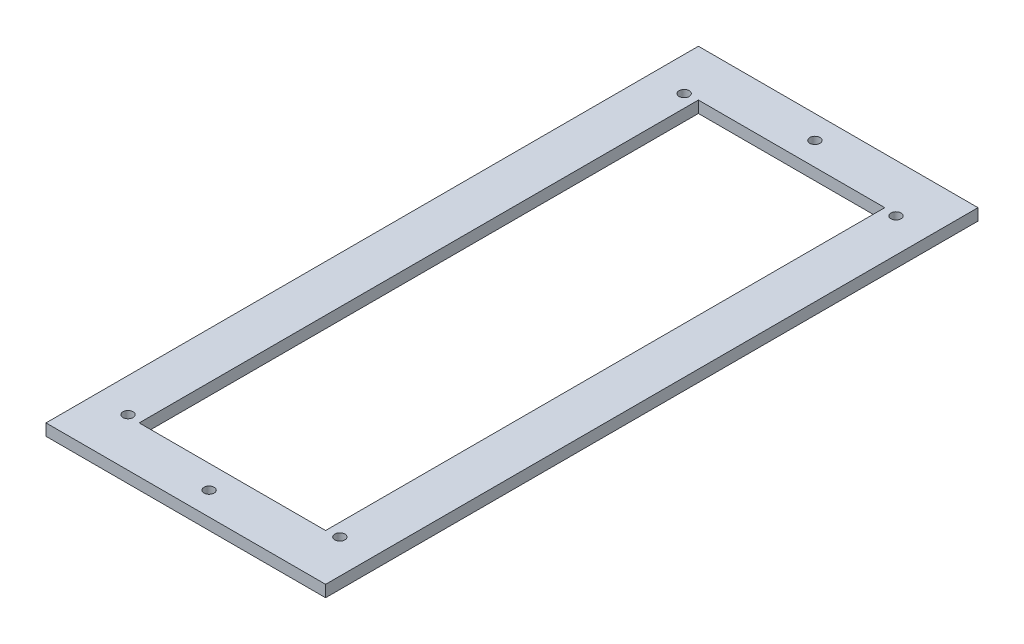
SolidWorks part; units mm, degrees
material "Birch Ply"
ref_plane "Front Plane" through (0, 0, 0) normal (0, 0, 1) x (1, 0, 0)
ref_plane "Top Plane" through (0, 0, 0) normal (0, 1, 0) x (1, 0, 0)
ref_plane "Right Plane" through (0, 0, 0) normal (1, 0, 0) x (0, 0, -1)
sketch "Sketch1" plane through (0, 0, 0) normal (0, 1, 0) x (1, 0, 0)
  line L0 (0, 0) -> (0, -177.8) construction
  line L1 (-38.1, 0) -> (38.1, 0)
  line L2 (-38.1, 0) -> (-38.1, -177.8)
  line L3 (-38.1, -177.8) -> (38.1, -177.8)
  line L4 (38.1, 0) -> (38.1, -177.8)
  line L7 (0, -55) -> (0, 55) construction
  line L8 (-55, 0) -> (55, 0) construction
  dimension "D1" = 76.2
  dimension "D2" = 177.8
extrude "Boss-Extrude1" add sketch "Sketch1" along normal blind 3.175
sketch "Sketch2" plane through (0, 3.175, 0) normal (0, 1, 0) x (1, 0, 0)
  line L0 (-38.1, 0) -> (-38.1, -177.8) construction
  line L1 (-25.4, -12.7) -> (25.4, -12.7)
  line L2 (-25.4, -12.7) -> (-25.4, -165.1)
  line L3 (-25.4, -165.1) -> (25.4, -165.1)
  line L4 (25.4, -12.7) -> (25.4, -165.1)
  line L5 (38.1, -177.8) -> (38.1, 0) construction
  line L6 (-38.1, -177.8) -> (38.1, -177.8) construction
  line L7 (38.1, 0) -> (-38.1, 0) construction
  line L8 (-1.7463, 0) -> (1.7463, 0) construction
  line L9 (0, 0) -> (0, -177.8) construction
  circle A0 centre (0, -6.35) radius 1.3843
  circle A1 centre (0, -171.45) radius 1.3843
  circle A2 centre (-28.8671, -13.1191) radius 1.3843
  circle A3 centre (28.8671, -13.1191) radius 1.3843
  circle A4 centre (-28.8671, -164.6809) radius 1.3843
  circle A5 centre (28.8671, -164.6809) radius 1.3843
  dimension "D6" = 2.7686
  dimension "D7" = 2.7686
  dimension "D9" = 2.7686
  dimension "D10" = 2.7686
  dimension "D11" = 2.7686
  dimension "D12" = 2.7686
  dimension "D1" = 12.7
  dimension "D2" = 12.7
  dimension "D3" = 12.7
  dimension "D4" = 12.7
  dimension "D5" = 6.35
  dimension "D8" = 6.35
  dimension "D13" = 28.8671
  dimension "D14" = 28.8671
  dimension "D15" = 28.8671
  dimension "D16" = 28.8671
  dimension "D17" = 13.1191
  dimension "D18" = 13.1191
  dimension "D19" = 13.1191
  dimension "D20" = 13.1191
extrude "Cut-Extrude1" cut sketch "Sketch2" against normal through all
